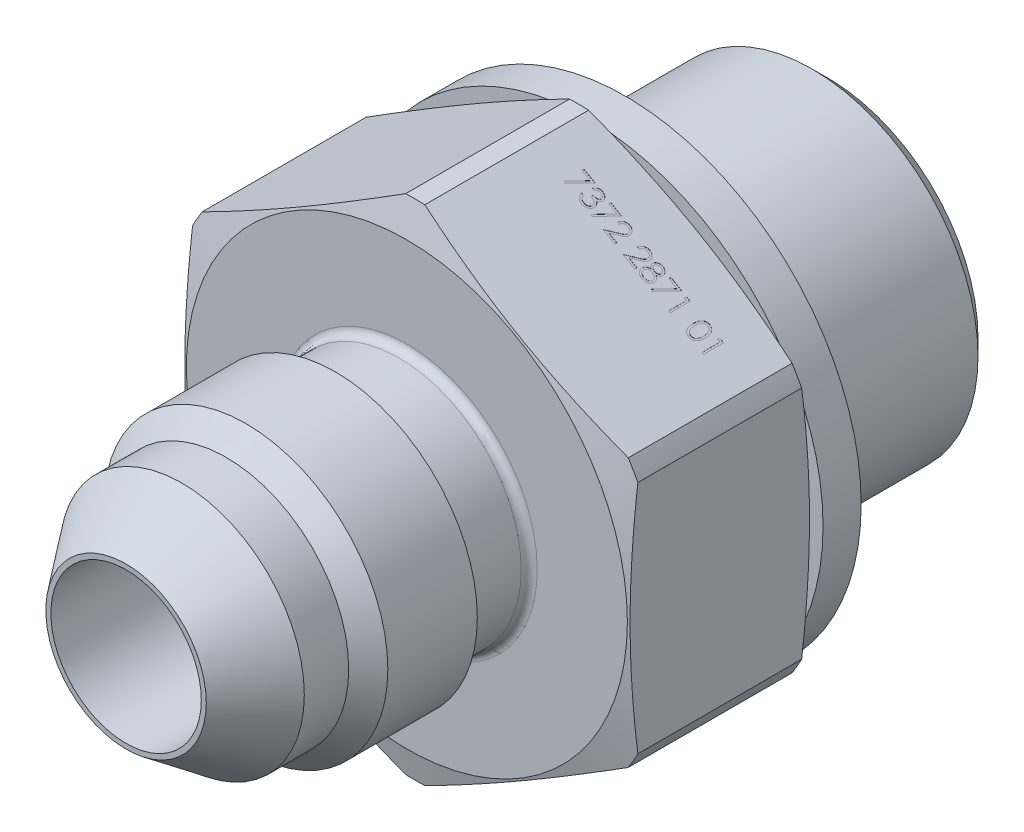
SolidWorks part; units mm, degrees
material "Plain Carbon Steel"
ref_plane "Front Plane" through (0, 0, 0) normal (0, 0, 1) x (1, 0, 0)
ref_plane "Top Plane" through (0, 0, 0) normal (0, 1, 0) x (1, 0, 0)
ref_plane "Right Plane" through (0, 0, 0) normal (1, 0, 0) x (0, 0, -1)
sketch "Sketch1" plane through (0, 0, 0) normal (1, 0, 0) x (0, 0, -1)
  line L0 (0, 0) -> (90.3331, 0) construction
  line L1 (0, 4) -> (2.7868, 6.1)
  line L2 (2.7868, 6.1) -> (5, 6.1)
  line L3 (5, 6.1) -> (5.975, 7.075)
  line L4 (5.975, 7.075) -> (10.4371, 7.075)
  line L5 (14.5, 3.75) -> (14.5, 1.5)
  line L6 (11, 6.1) -> (13.6, 6.1)
  line L7 (14, 6.5) -> (14, 10.994)
  line L8 (14.4169, 12.55) -> (22.5831, 12.55)
  line L9 (23, 10.994) -> (23, 7.25)
  line L10 (26.5, 8.275) -> (34.2, 8.275)
  line L11 (35, 7.475) -> (35, 7)
  line L12 (35, 7) -> (31.5359, 5)
  line L13 (14.5, 3.75) -> (0, 3.75)
  line L14 (0, 3.75) -> (0, 4)
  line L15 (34.2, 8.275) -> (35, 7.475)
  line L16 (14.4169, 12.55) -> (14, 10.994)
  line L17 (22.5831, 12.55) -> (23, 10.994)
  line L18 (19.5, 3.3357) -> (20.5, 5)
  line L19 (20.5, 5) -> (31.5359, 5)
  line L20 (26.5, 8.275) -> (25.475, 7.25)
  line L21 (25.475, 7.25) -> (23, 7.25)
  line L22 (10.4371, 7.075) -> (11, 6.1)
  line L23 (14.5, 1.5) -> (19.5, 1.5)
  line L24 (19.5, 3.3357) -> (19.5, 1.5)
  arc A0 (13.6, 6.1) -> (14, 6.5) centre (13.6, 6.5) ccw
  point P14 (35, 8.275)
  dimension "D28" = 0.4
  dimension "D1" = 25.1
  dimension "D2" = 16.55
  dimension "D3" = 8
  dimension "D4" = 14
  dimension "D5" = 30
  dimension "D6" = 12
  dimension "D7" = 35
  dimension "D8" = 60
  dimension "D9" = 5
  dimension "D10" = 12.2
  dimension "D11" = 14.15
  dimension "D12" = 14
  dimension "D13" = 7.5
  dimension "D14" = 37
  dimension "D15" = 15
  dimension "D16" = 15
  dimension "D18" = 1.556
  dimension "D19" = 10
  dimension "D20" = 14.5
  dimension "D21" = 59
  dimension "D22" = 8.5
  dimension "D23" = 45
  dimension "D24" = 14.5
  dimension "D25" = 45
  dimension "D26" = 3
  dimension "D27" = 12.2
  dimension "D29" = 9
  dimension "D30" = 3
  dimension "D31" = 5
  dimension "D32" = 15.5
revolve "Revolve1" add sketch "Sketch1" angle 360 about L0
cosmetic thread "Cosmetic Thread1" parameters "D2"=13
cosmetic thread "Cosmetic Thread2" parameters "D2"=15.2
sketch "Sketch2" plane through (0, 0, -14) normal (0, 0, 1) x (1, 0, 0)
  line L1 (0, 12.8172) -> (-11.1, 6.4086)
  line L2 (-11.1, 6.4086) -> (-11.1, -6.4086)
  line L3 (-11.1, -6.4086) -> (0, -12.8172)
  line L4 (0, -12.8172) -> (11.1, -6.4086)
  line L5 (11.1, -6.4086) -> (11.1, 6.4086)
  line L6 (11.1, 6.4086) -> (0, 12.8172)
  circle A0 centre (0, 0) radius 11.1 construction
  dimension "D1" = 22.2
extrude "Extrude2" cut sketch "Sketch2" against normal up to surface (9 mm away) flip side to cut up to face at (10.994, 0, -23)
sketch "Sketch3" plane through (0, 0, -23) normal (0, 0, -1) x (-1, 0, 0)
  circle A0 centre (0, 0) radius 11.75
  circle A1 centre (0, 0) radius 9.6
  dimension "D1" = 23.5
  dimension "D2" = 19.2
extrude "Extrude3" add sketch "Sketch3" along normal blind 1.9 separate body
sketch "Sketch5" plane through (5.55, 9.6129, 0) normal (0.5, 0.866, 0) x (0.866, -0.5, 0)
  line L0 (-5.7258, 19.8095) -> (5.856, 19.8095) construction
  line L1 (5.856, 14.4169) -> (5.856, 22.5831) construction
  text T0 "7372 2871 01\r\n" font "Century Gothic" height 1
extrude "Cut-Extrude1" cut sketch "Sketch5" against normal blind 0.01
sketch "Sketch6" plane through (0, 0, 0) normal (1, 0, 0) x (0, 0, -1)
  line L0 (0, 0) -> (40.5913, 0) construction
  line L1 (24.9, -11.75) -> (24.9, 11.75) construction
  circle A0 centre (24.1, 8.45) radius 1.2
  dimension "D1" = 14.5
  dimension "D2" = 2.4
  dimension "D3" = 0.8
revolve "Revolve2" add sketch "Sketch6" angle 360 about L0
